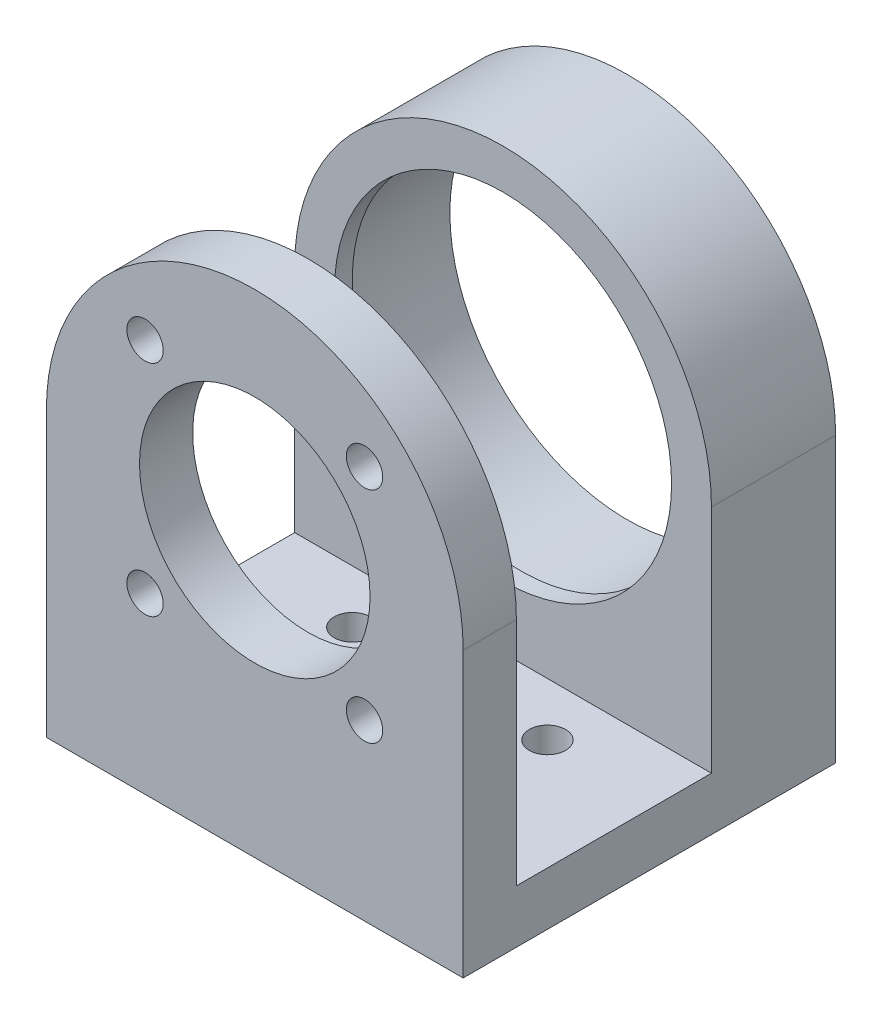
SolidWorks part; units mm, degrees
material "6061 合金"
ref_plane "前视基准面" through (0, 0, 0) normal (0, 0, 1) x (1, 0, 0)
ref_plane "上视基准面" through (0, 0, 0) normal (0, 1, 0) x (1, 0, 0)
ref_plane "右视基准面" through (0, 0, 0) normal (1, 0, 0) x (0, 0, -1)
sketch "草图2" plane through (0, 0, 0) normal (0, 0, 1) x (1, 0, 0)
  line L3 (-23.5, 32) -> (-23.5, 0)
  line L4 (-23.5, 0) -> (23.5, 0)
  line L5 (23.5, 0) -> (23.5, 32)
  line L6 (0, 63.3985) -> (0, -5.6388) construction
  arc A1 (23.5, 32) -> (-23.5, 32) centre (0, 32) ccw
  point P4 (0, 0)
  dimension "D3" = 47
  dimension "D1" = 32
extrude "凸台-拉伸1" add sketch "草图2" along normal blind 36
sketch "草图3" plane through (0, 0, 36) normal (0, 0, 1) x (1, 0, 0)
  circle A0 centre (0, 32) radius 13
  dimension "D1" = 26
extrude "切除-拉伸1" cut sketch "草图3" against normal blind 20
hole_wizard "M4 间隙孔1" positions "草图5" profile "草图6" hole size "M4" standard "GB"
sketch "草图5" plane through (0, 0, 36) normal (0, 0, 1) x (1, 0, 0)
  circle A0 centre (0, 32) radius 17.5 construction
  point P22 (-12.3744, 44.3744)
  point P24 (12.3744, 44.3744)
  point P26 (-12.3744, 19.6256)
  point P28 (12.3744, 19.6256)
  dimension "D1" = 35
  dimension "D2" = 90
sketch "草图6" plane through (12.3744, 19.6256, 36) normal (1, 0, 0) x (0, -1, 0)
  line L0 (0, 0) -> (0, 21.2318)
  line L1 (0, 21.2318) -> (2.05, 20)
  line L2 (2.05, 20) -> (2.05, 0)
  line L5 (2.05, 0) -> (0, 0)
  line L10 (0, 21.2318) -> (-2.05, 20) construction
  line L11 (0, -6.35) -> (0, 107.95) construction
  dimension "孔直径" = 4.1
  dimension "孔深度" = 20
  dimension "导头角度" = 118
sketch "草图17" plane through (23.5, 0, 0) normal (1, 0, 0) x (0, 0, -1)
  line L0 (0, 55.5) -> (-36, 55.5) construction
  line L1 (-30, 55.5) -> (-8, 55.5)
  line L2 (-30, 55.5) -> (-30, 10)
  line L3 (-30, 10) -> (-8, 10)
  line L4 (-8, 55.5) -> (-8, 10)
  line L5 (-36, 55.5) -> (-36, 32) construction
  line L6 (0, 32) -> (0, 55.5) construction
  line L7 (-36, 0) -> (0, 0) construction
  dimension "D1" = 6
  dimension "D2" = 8
  dimension "D3" = 10
extrude "切除-拉伸4" cut sketch "草图17" against normal through all
hole_wizard "M4 间隙孔2" positions "草图19" profile "草图20" hole size "M4" standard "GB"
sketch "草图19" plane through (0, 10, 0) normal (0, 1, 0) x (1, 0, 0)
  line L0 (-23.5, -36) -> (23.5, -36) construction
  line L1 (23.5, -30) -> (23.5, -8) construction
  point P0 (-11, -14)
  point P2 (11, -14)
  point P4 (11, -24)
  point P6 (-11, -24)
  dimension "D1" = 22
  dimension "D2" = 10
  dimension "D3" = 12
  dimension "D4" = 12.5
sketch "草图20" plane through (-11, 10, 14) normal (1, 0, 0) x (0, 0, 1)
  line L0 (0, 0) -> (0, 11.3318)
  line L1 (0, 11.3318) -> (2.05, 10.1)
  line L2 (2.05, 10.1) -> (2.05, 0)
  line L5 (2.05, 0) -> (0, 0)
  line L10 (0, 11.3318) -> (-2.05, 10.1) construction
  line L11 (0, -6.35) -> (0, 107.95) construction
  dimension "孔直径" = 4.1
  dimension "孔深度" = 10.1
  dimension "导头角度" = 118
sketch "草图21" plane through (0, 0, 0) normal (0, 0, -1) x (-1, 0, 0)
  circle A0 centre (0, 32) radius 20
  dimension "D1" = 40
extrude "切除-拉伸5" cut sketch "草图21" against normal blind 6
sketch "草图22" plane through (0, 0, 6) normal (0, 0, -1) x (-1, 0, 0)
  circle A0 centre (0, 32) radius 19
  dimension "D1" = 38
extrude "切除-拉伸6" cut sketch "草图22" against normal blind 10
sketch "草图26" plane through (0, 10, 0) normal (0, 1, 0) x (1, 0, 0)
  line L1 (-23.5, -8) -> (23.5, -8)
  line L2 (-23.5, -8) -> (-23.5, -30)
  line L3 (-23.5, -30) -> (23.5, -30)
  line L4 (23.5, -8) -> (23.5, -30)
extrude "切除-拉伸8" cut sketch "草图26" against normal blind 4
sketch "草图27" plane through (0, 0, 0) normal (0, 0, -1) x (-1, 0, 0)
  line L0 (-23.5, 32) -> (-23.5, 0)
  line L1 (-23.5, 0) -> (23.5, 0)
  line L2 (23.5, 0) -> (23.5, 32)
  circle A0 centre (0, 32) radius 20
  arc A1 (23.5, 32) -> (-23.5, 32) centre (0, 32) ccw
  dimension "D1" = 40
extrude "凸台-拉伸2" add sketch "草图27" along normal blind 6
ref_point "点1"
